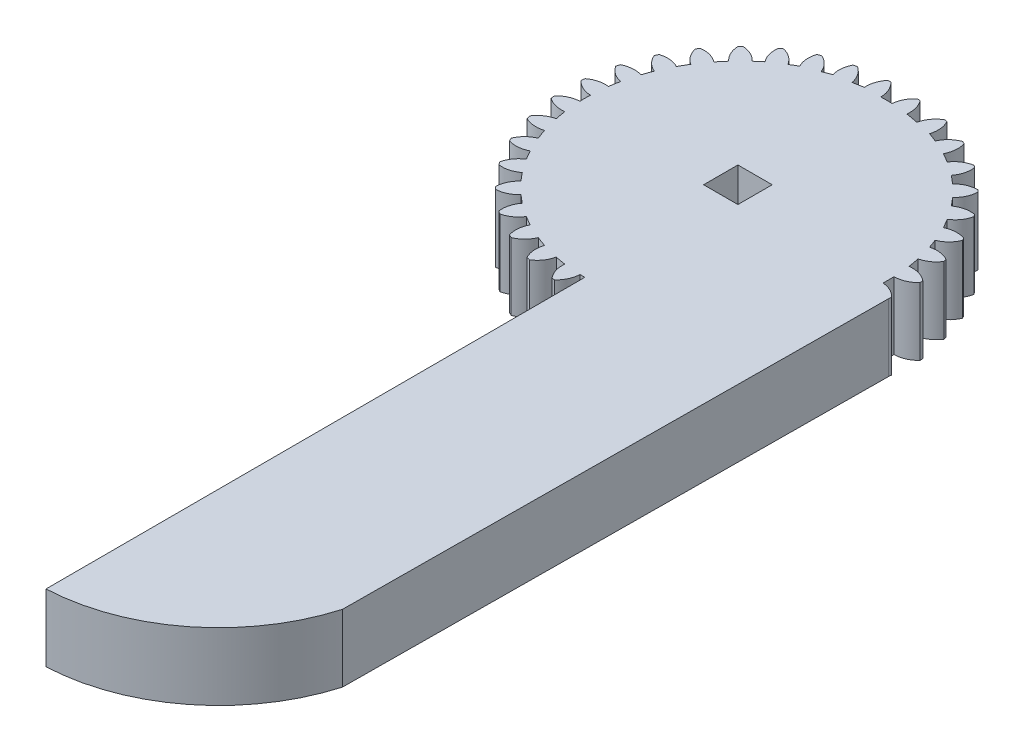
SolidWorks part; units mm, degrees
ref_plane "Front Plane" through (0, 0, 0) normal (0, 0, 1) x (1, 0, 0)
ref_plane "Top Plane" through (0, 0, 0) normal (0, 1, 0) x (1, 0, 0)
ref_plane "Right Plane" through (0, 0, 0) normal (1, 0, 0) x (0, 0, -1)
sketch "Sketch1" plane through (0, 0, 0) normal (0, 1, 0) x (1, 0, 0)
  line L1 (3.1226, 5.3296) -> (6.3526, 5.3296)
  line L2 (3.1226, 5.3296) -> (3.1226, 2.0996)
  line L3 (3.1226, 2.0996) -> (6.3526, 2.0996)
  line L4 (6.3526, 5.3296) -> (6.3526, 2.0996)
  arc A0 (-8.4629, 9.0479) -> (-8.8027, 8.1141) centre (4.7376, 3.7146) ccw
  arc A1 (-8.8027, 8.1141) -> (-10.5974, 7.9673) centre (-9.5244, 5.8929) ccw
  arc A2 (-10.5974, 7.9673) -> (-10.6872, 7.6321) centre (4.7283, 3.6812) ccw
  arc A3 (-10.6872, 7.6321) -> (-9.2064, 6.6077) centre (-8.7208, 8.8921) ccw
  arc A4 (-9.2064, 6.6077) -> (-9.3789, 5.629) centre (4.7196, 3.6476) ccw
  arc A5 (-9.3789, 5.629) -> (-11.1208, 5.1729) centre (-9.704, 3.3163) ccw
  arc A6 (-11.1208, 5.1729) -> (-11.1511, 4.8271) centre (4.7163, 3.6131) ccw
  arc A7 (-11.1511, 4.8271) -> (-9.5149, 4.0754) centre (-9.4334, 6.4094) ccw
  arc A8 (-9.5149, 4.0754) -> (-9.5149, 3.0817) centre (4.7136, 3.5785) ccw
  arc A9 (-9.5149, 3.0817) -> (-11.1511, 2.33) centre (-9.4334, 0.7476) ccw
  arc A10 (-11.1511, 2.33) -> (-11.1208, 1.9842) centre (4.7163, 3.544) ccw
  arc A11 (-11.1208, 1.9842) -> (-9.3789, 1.528) centre (-9.704, 3.8408) ccw
  arc A12 (-9.3789, 1.528) -> (-9.2064, 0.5494) centre (4.7196, 3.5095) ccw
  arc A13 (-9.2064, 0.5494) -> (-10.6872, -0.475) centre (-8.7208, -1.735) ccw
  arc A14 (-10.6872, -0.475) -> (-10.5974, -0.8103) centre (4.7283, 3.4759) ccw
  arc A15 (-10.5974, -0.8103) -> (-8.8027, -0.957) centre (-9.5244, 1.2642) ccw
  arc A16 (-8.8027, -0.957) -> (-8.4629, -1.8908) centre (4.7376, 3.4425) ccw
  arc A17 (-8.4629, -1.8908) -> (-9.7433, -3.1568) centre (-7.588, -4.0562) ccw
  arc A18 (-9.7433, -3.1568) -> (-9.5966, -3.4714) centre (4.7519, 3.4109) ccw
  arc A19 (-9.5966, -3.4714) -> (-7.8038, -3.3043) centre (-8.9002, -1.2422) ccw
  arc A20 (-7.8038, -3.3043) -> (-7.3069, -4.1649) centre (4.7669, 3.3797) ccw
  arc A21 (-7.3069, -4.1649) -> (-8.3481, -5.634) centre (-6.0693, -6.1455) ccw
  arc A22 (-8.3481, -5.634) -> (-8.149, -5.9183) centre (4.7865, 3.3511) ccw
  arc A23 (-8.149, -5.9183) -> (-6.4124, -5.4424) centre (-7.8502, -3.602) ccw
  arc A24 (-6.4124, -5.4424) -> (-5.7736, -6.2036) centre (4.8066, 3.3229) ccw
  arc A25 (-5.7736, -6.2036) -> (-6.5438, -7.8312) centre (-4.2109, -7.9392) ccw
  arc A26 (-6.5438, -7.8312) -> (-6.2984, -8.0766) centre (4.8309, 3.2981) ccw
  arc A27 (-6.2984, -8.0766) -> (-4.6708, -7.3064) centre (-6.4064, -5.7437) ccw
  arc A28 (-4.6708, -7.3064) -> (-3.9096, -7.9452) centre (4.8557, 3.2738) ccw
  arc A29 (-3.9096, -7.9452) -> (-4.3855, -9.6818) centre (-2.0692, -9.383) ccw
  arc A30 (-4.3855, -9.6818) -> (-4.1012, -9.8808) centre (4.8839, 3.2537) ccw
  arc A31 (-4.1012, -9.8808) -> (-2.6321, -8.8397) centre (-4.6127, -7.6021) ccw
  arc A32 (-2.6321, -8.8397) -> (-1.7715, -9.3365) centre (4.9124, 3.2341) ccw
  arc A33 (-1.7715, -9.3365) -> (-1.9386, -11.1294) centre (0.2906, -10.433) ccw
  arc A34 (-1.9386, -11.1294) -> (-1.624, -11.2761) centre (4.9437, 3.2191) ccw
  arc A35 (-1.624, -11.2761) -> (-0.358, -9.9956) centre (-2.5235, -9.1208) ccw
  arc A36 (-0.358, -9.9956) -> (0.5758, -10.3355) centre (4.9753, 3.2048) ccw
  arc A37 (0.5758, -10.3355) -> (0.7225, -12.1302) centre (2.7969, -11.0572) ccw
  arc A38 (0.7225, -12.1302) -> (1.0578, -12.22) centre (5.0087, 3.1955) ccw
  arc A39 (1.0578, -12.22) -> (2.0822, -10.7392) centre (-0.2023, -10.2536) ccw
  arc A40 (2.0822, -10.7392) -> (3.0608, -10.9117) centre (5.0422, 3.1868) ccw
  arc A41 (3.0608, -10.9117) -> (3.5921, -12.6536) centre (5.3836, -11.1553) ccw
  arc A42 (3.5921, -12.6536) -> (3.8688, -12.6778) centre (5.1173, 3.1868) ccw
  arc A43 (3.8688, -12.6778) -> (4.6204, -11.044) centre (2.2864, -10.9601) ccw
  arc A44 (4.6204, -11.044) -> (5.5392, -11.0416) centre (5.0423, 3.1868) ccw
  arc A45 (5.5392, -11.0416) -> (6.3659, -12.6778) centre (7.8698, -10.891) ccw
  arc A46 (6.3659, -12.6778) -> (6.6426, -12.6536) centre (5.1173, 3.1868) ccw
  arc A47 (6.6426, -12.6536) -> (7.0988, -10.9117) centre (4.786, -11.2368) ccw
  arc A48 (7.0988, -10.9117) -> (8.0035, -10.7522) centre (5.0802, 3.1816) ccw
  arc A49 (8.0035, -10.7522) -> (9.0949, -12.2151) centre (10.2723, -10.1981) ccw
  arc A50 (9.0949, -12.2151) -> (9.3632, -12.1432) centre (5.1104, 3.1918) ccw
  arc A51 (9.3632, -12.1432) -> (9.5099, -10.3485) centre (7.2888, -11.0702) ccw
  arc A52 (9.5099, -10.3485) -> (10.3733, -10.0343) centre (5.0748, 3.1801) ccw
  arc A53 (10.3733, -10.0343) -> (11.7064, -11.297) centre (12.5166, -9.1066) ccw
  arc A54 (11.7064, -11.297) -> (11.9581, -11.1796) centre (5.107, 3.1839) ccw
  arc A55 (11.9581, -11.1796) -> (11.7983, -9.4007) centre (9.7289, -10.4832) ccw
  arc A56 (11.7983, -9.4007) -> (12.5474, -8.9681) centre (5.0568, 3.1392) ccw
  arc A57 (12.5474, -8.9681) -> (14.0856, -9.9905) centre (14.5039, -7.6928) ccw
  arc A58 (14.0856, -9.9905) -> (14.3131, -9.8312) centre (5.072, 3.1244) ccw
  arc A59 (14.3131, -9.8312) -> (13.8524, -8.1143) centre (11.9968, -9.5324) ccw
  arc A60 (13.8524, -8.1143) -> (14.5276, -7.5474) centre (5.0396, 3.0673) ccw
  arc A61 (14.5276, -7.5474) -> (16.2323, -8.3032) centre (16.2479, -5.9678) ccw
  arc A62 (16.2323, -8.3032) -> (16.4287, -8.1069) centre (5.0782, 3.0472) ccw
  arc A63 (16.4287, -8.1069) -> (15.6928, -6.5108) centre (14.0957, -8.2149) ccw
  arc A64 (15.6928, -6.5108) -> (16.2617, -5.8331) centre (5.0782, 2.9773) ccw
  arc A65 (16.2617, -5.8331) -> (18.083, -6.2906) centre (17.6933, -3.9879) ccw
  arc A66 (18.083, -6.2906) -> (18.2423, -6.0631) centre (5.1274, 2.9505) ccw
  arc A67 (18.2423, -6.0631) -> (17.2416, -4.6199) centre (15.9635, -6.5746) ccw
  arc A68 (17.2416, -4.6199) -> (17.6956, -3.8334) centre (5.1448, 2.8877) ccw
  arc A69 (17.6956, -3.8334) -> (19.5697, -3.9701) centre (18.7882, -1.7693) ccw
  arc A70 (19.5697, -3.9701) -> (19.6871, -3.7184) centre (5.2062, 2.8809) ccw
  arc A71 (19.6871, -3.7184) -> (18.4655, -2.4771) centre (17.5318, -4.6178) ccw
  arc A72 (18.4655, -2.4771) -> (19.0015, -1.58) centre (6.5204, 5.2696) ccw
  arc A73 (19.0015, -1.58) -> (20.7489, -1.3501) centre (19.5931, 0.6793) ccw
  arc A74 (20.7489, -1.3501) -> (20.8208, -1.0819) centre (5.4139, 2.9026) ccw
  arc A75 (20.8208, -1.0819) -> (19.2773, -0.045) centre (18.8543, -2.3419) ccw
  arc A76 (19.2773, -0.045) -> (19.457, 0.9703) centre (5.3571, 2.9424) ccw
  arc A77 (19.457, 0.9703) -> (21.1306, 1.505) centre (19.6353, 3.299) ccw
  arc A78 (21.1306, 1.505) -> (21.1548, 1.7816) centre (5.2902, 3.0302) ccw
  arc A79 (21.1548, 1.7816) -> (19.588, 2.5299) centre (19.4371, 0.1993) ccw
  arc A80 (19.588, 2.5299) -> (19.5887, 3.5643) centre (5.3606, 3.0559) ccw
  arc A81 (19.5887, 3.5643) -> (21.2992, 4.3175) centre (19.5814, 5.8998) ccw
  arc A82 (21.2992, 4.3175) -> (21.275, 4.5942) centre (5.4345, 3.0689) ccw
  arc A83 (21.275, 4.5942) -> (19.4527, 5.118) centre (19.7742, 2.8047) ccw
  arc A84 (19.4527, 5.118) -> (19.2696, 6.1496) centre (5.3525, 3.1481) ccw
  arc A85 (19.2696, 6.1496) -> (20.6965, 7.1618) centre (18.7301, 8.4219) ccw
  arc A86 (20.6965, 7.1618) -> (20.6246, 7.4301) centre (5.2896, 3.1774) ccw
  arc A87 (20.6246, 7.4301) -> (18.8522, 7.6522) centre (19.4701, 5.4) ccw
  arc A88 (18.8522, 7.6522) -> (18.5545, 8.4711) centre (5.329, 3.2004) ccw
  arc A89 (18.5545, 8.4711) -> (19.8496, 9.743) centre (17.6943, 10.6424) ccw
  arc A90 (19.8496, 9.743) -> (19.7322, 9.9947) centre (5.3687, 3.1436) ccw
  arc A91 (19.7322, 9.9947) -> (17.9104, 9.8914) centre (18.943, 7.7966) ccw
  arc A92 (17.9104, 9.8914) -> (17.4135, 10.752) centre (5.3398, 3.2075) ccw
  arc A93 (17.4135, 10.752) -> (18.4547, 12.2211) centre (16.1759, 12.7326) ccw
  arc A94 (18.4547, 12.2211) -> (18.2954, 12.4487) centre (5.3398, 3.2075) ccw
  arc A95 (18.2954, 12.4487) -> (16.519, 12.0295) centre (17.9009, 10.1467) ccw
  arc A96 (16.519, 12.0295) -> (15.8803, 12.7908) centre (5.3, 3.2643) ccw
  arc A97 (15.8803, 12.7908) -> (16.6505, 14.4184) centre (14.3175, 14.5264) ccw
  arc A98 (16.6505, 14.4184) -> (16.4541, 14.6148) centre (5.3, 3.2643) ccw
  arc A99 (16.4541, 14.6148) -> (14.7775, 13.8936) centre (16.4653, 12.2793) ccw
  arc A100 (14.7775, 13.8936) -> (14.0162, 14.5323) centre (5.251, 3.3133) ccw
  arc A101 (14.0162, 14.5323) -> (14.4921, 16.2689) centre (12.1759, 15.9702) ccw
  arc A102 (14.4921, 16.2689) -> (14.2646, 16.4282) centre (5.251, 3.3133) ccw
  arc A103 (14.2646, 16.4282) -> (12.7387, 15.4268) centre (14.6812, 14.1302) ccw
  arc A104 (12.7387, 15.4268) -> (11.8781, 15.9237) centre (5.1942, 3.3531) ccw
  arc A105 (11.8781, 15.9237) -> (12.0452, 17.7166) centre (9.816, 17.0201) ccw
  arc A106 (12.0452, 17.7166) -> (11.7935, 17.834) centre (5.1942, 3.3531) ccw
  arc A107 (11.7935, 17.834) -> (10.4647, 16.5828) centre (12.6028, 15.6432) ccw
  arc A108 (10.4647, 16.5828) -> (9.5963, 16.9013) centre (5.1314, 3.3824) ccw
  arc A109 (9.5963, 16.9013) -> (9.447, 18.688) centre (7.3725, 17.6151) ccw
  arc A110 (9.447, 18.688) -> (9.1787, 18.7599) centre (5.1942, 3.3531) ccw
  arc A111 (9.1787, 18.7599) -> (8.0731, 17.2362) centre (10.3559, 16.7428) ccw
  arc A112 (8.0731, 17.2362) -> (6.9219, 17.4412) centre (5.0039, 3.3339) ccw
  arc A113 (6.9219, 17.4412) -> (6.4622, 19.1564) centre (4.6056, 17.7395) ccw
  arc A114 (6.4622, 19.1564) -> (6.1855, 19.1806) centre (4.9369, 3.3159) ccw
  arc A115 (6.1855, 19.1806) -> (5.3712, 17.6066) centre (7.6975, 17.4007) ccw
  arc A116 (5.3712, 17.6066) -> (4.3071, 17.6071) centre (4.8319, 3.3797) ccw
  arc A117 (4.3071, 17.6071) -> (3.5541, 19.3072) centre (1.9717, 17.5894) ccw
  arc A118 (3.5541, 19.3072) -> (3.2774, 19.283) centre (4.8026, 3.4425) ccw
  arc A119 (3.2774, 19.283) -> (2.7476, 17.6093) centre (5.0758, 17.793) ccw
  arc A120 (2.7476, 17.6093) -> (1.7668, 17.437) centre (4.7196, 3.5095) ccw
  arc A121 (1.7668, 17.437) -> (0.7291, 18.9854) centre (-0.5309, 17.019) ccw
  arc A122 (0.7291, 18.9854) -> (0.3962, 18.9022) centre (4.4202, 3.5056) ccw
  arc A123 (0.3962, 18.9022) -> (0.2306, 17.1685) centre (2.4706, 17.8292) ccw
  arc A124 (0.2306, 17.1685) -> (-0.5756, 16.8633) centre (4.8649, 3.7067) ccw
  arc A125 (-0.5756, 16.8633) -> (-1.8618, 18.1954) centre (-2.7612, 16.0401) ccw
  arc A126 (-1.8618, 18.1954) -> (-2.1768, 18.0534) centre (4.5211, 3.6178) ccw
  arc A127 (-2.1768, 18.0534) -> (-2.0289, 16.2975) centre (0.0524, 17.357) ccw
  arc A128 (-2.0289, 16.2975) -> (-2.7236, 15.8848) centre (4.892, 3.8557) ccw
  arc A129 (-2.7236, 15.8848) -> (-4.207, 16.9491) centre (-4.7185, 14.6703) ccw
  arc A130 (-4.207, 16.9491) -> (-4.4929, 16.751) centre (4.7146, 3.7714) ccw
  arc A131 (-4.4929, 16.751) -> (-4.022, 15.0209) centre (-2.1766, 16.4522) ccw
  arc A132 (-4.022, 15.0209) -> (-4.6708, 14.4634) centre (4.9277, 3.9485) ccw
  arc A133 (-4.6708, 14.4634) -> (-6.2984, 15.2337) centre (-6.4064, 12.9007) ccw
  arc A134 (-6.2984, 15.2337) -> (-6.5438, 14.9883) centre (4.8309, 3.8589) ccw
  arc A135 (-6.5438, 14.9883) -> (-5.7736, 13.3607) centre (-4.2109, 15.0963) ccw
  arc A136 (-5.7736, 13.3607) -> (-6.4124, 12.5994) centre (4.8066, 3.8342) ccw
  arc A137 (-6.4124, 12.5994) -> (-8.149, 13.0753) centre (-7.8502, 10.759) ccw
  arc A138 (-8.149, 13.0753) -> (-8.3481, 12.791) centre (4.7865, 3.806) ccw
  arc A139 (-8.3481, 12.791) -> (-7.3069, 11.3219) centre (-6.0693, 13.3025) ccw
  arc A140 (-7.3069, 11.3219) -> (-7.8038, 10.4613) centre (4.7669, 3.7774) ccw
  arc A141 (-7.8038, 10.4613) -> (-9.5966, 10.6284) centre (-8.9002, 8.3992) ccw
  arc A142 (-9.5966, 10.6284) -> (-9.7433, 10.3139) centre (4.7519, 3.7461) ccw
  arc A143 (-9.7433, 10.3139) -> (-8.4629, 9.0479) centre (-7.588, 11.2133) ccw
  point P288 (0, 0)
  dimension "D6" = 1.5596
  dimension "D33" = 1.5596
  dimension "D39" = 1.5596
  dimension "D1" = 3.23
  dimension "D2" = 3.23
  dimension "D3" = 1.615
  dimension "D4" = 1.615
  dimension "D5" = 1.5596
  dimension "D7" = 1.5596
  dimension "D8" = 1.5596
  dimension "D9" = 1.5596
  dimension "D10" = 1.5596
  dimension "D11" = 1.5596
  dimension "D12" = 1.5596
  dimension "D13" = 1.5596
  dimension "D14" = 1.5596
  dimension "D15" = 1.5596
  dimension "D16" = 1.5596
  dimension "D17" = 1.5596
  dimension "D18" = 1.5596
  dimension "D19" = 1.5596
  dimension "D20" = 1.5596
  dimension "D21" = 1.5596
  dimension "D22" = 1.5596
  dimension "D23" = 1.5596
  dimension "D24" = 1.5596
  dimension "D25" = 1.5596
  dimension "D26" = 1.5596
  dimension "D27" = 1.5596
  dimension "D28" = 1.5596
  dimension "D29" = 1.5596
  dimension "D30" = 1.5596
  dimension "D31" = 1.5596
  dimension "D32" = 1.5596
  dimension "D34" = 1.5596
  dimension "D35" = 1.5596
  dimension "D36" = 1.5596
  dimension "D37" = 1.5596
  dimension "D38" = 1.5596
  dimension "D40" = 1.5596
extrude "Boss-Extrude1" add sketch "Sketch1" along normal blind 6.35
sketch "Sketch3" plane through (0, 6.35, 0) normal (0, 1, 0) x (1, 0, 0)
  line L0 (5.1234, -61.85) -> (5.0798, -11.0502)
  line L1 (20.7489, -49.5398) -> (21.1306, 1.505)
  arc A0 (5.1234, -61.85) -> (20.7489, -49.5398) centre (4.3767, -44.8304) ccw
  arc A144 (-9.7433, 10.3139) -> (-8.4629, 9.0479) centre (-7.588, 11.2133) ccw
  arc A145 (-8.4629, 9.0479) -> (-8.8027, 8.1141) centre (4.7376, 3.7146) ccw
  arc A146 (-8.8027, 8.1141) -> (-10.5974, 7.9673) centre (-9.5244, 5.8929) ccw
  arc A147 (-10.5974, 7.9673) -> (-10.6872, 7.6321) centre (4.7283, 3.6812) ccw
  arc A148 (-10.6872, 7.6321) -> (-9.2064, 6.6077) centre (-8.7208, 8.8921) ccw
  arc A149 (-9.2064, 6.6077) -> (-9.3789, 5.629) centre (4.7196, 3.6476) ccw
  arc A150 (-9.3789, 5.629) -> (-11.1208, 5.1729) centre (-9.704, 3.3163) ccw
  arc A151 (-11.1208, 5.1729) -> (-11.1511, 4.8271) centre (4.7163, 3.6131) ccw
  arc A152 (-11.1511, 4.8271) -> (-9.5149, 4.0754) centre (-9.4334, 6.4094) ccw
  arc A153 (-9.5149, 4.0754) -> (-9.5149, 3.0817) centre (4.7136, 3.5785) ccw
  arc A154 (-9.5149, 3.0817) -> (-11.1511, 2.33) centre (-9.4334, 0.7476) ccw
  arc A155 (-11.1511, 2.33) -> (-11.1208, 1.9842) centre (4.7163, 3.544) ccw
  arc A156 (-11.1208, 1.9842) -> (-9.3789, 1.528) centre (-9.704, 3.8408) ccw
  arc A157 (-9.3789, 1.528) -> (-9.2064, 0.5494) centre (4.7196, 3.5095) ccw
  arc A158 (-9.2064, 0.5494) -> (-10.6872, -0.475) centre (-8.7208, -1.735) ccw
  arc A159 (-10.6872, -0.475) -> (-10.5974, -0.8103) centre (4.7283, 3.4759) ccw
  arc A160 (-10.5974, -0.8103) -> (-8.8027, -0.957) centre (-9.5244, 1.2642) ccw
  arc A161 (-8.8027, -0.957) -> (-8.4629, -1.8908) centre (4.7376, 3.4425) ccw
  arc A162 (-8.4629, -1.8908) -> (-9.7433, -3.1568) centre (-7.588, -4.0562) ccw
  arc A163 (-9.7433, -3.1568) -> (-9.5966, -3.4714) centre (4.7519, 3.4109) ccw
  arc A164 (-9.5966, -3.4714) -> (-7.8038, -3.3043) centre (-8.9002, -1.2422) ccw
  arc A165 (-7.8038, -3.3043) -> (-7.3069, -4.1649) centre (4.7669, 3.3797) ccw
  arc A166 (-7.3069, -4.1649) -> (-8.3481, -5.634) centre (-6.0693, -6.1455) ccw
  arc A167 (-8.3481, -5.634) -> (-8.149, -5.9183) centre (4.7865, 3.3511) ccw
  arc A168 (-8.149, -5.9183) -> (-6.4124, -5.4424) centre (-7.8502, -3.602) ccw
  arc A169 (-6.4124, -5.4424) -> (-5.7736, -6.2036) centre (4.8066, 3.3229) ccw
  arc A170 (-5.7736, -6.2036) -> (-6.5438, -7.8312) centre (-4.2109, -7.9392) ccw
  arc A171 (-6.5438, -7.8312) -> (-6.2984, -8.0766) centre (4.8309, 3.2981) ccw
  arc A172 (-6.2984, -8.0766) -> (-4.6708, -7.3064) centre (-6.4064, -5.7437) ccw
  arc A173 (-4.6708, -7.3064) -> (-3.9096, -7.9452) centre (4.8557, 3.2738) ccw
  arc A174 (-3.9096, -7.9452) -> (-4.3855, -9.6818) centre (-2.0692, -9.383) ccw
  arc A175 (-4.3855, -9.6818) -> (-4.1012, -9.8808) centre (4.8839, 3.2537) ccw
  arc A176 (-4.1012, -9.8808) -> (-2.6321, -8.8397) centre (-4.6127, -7.6021) ccw
  arc A177 (-2.6321, -8.8397) -> (-1.7715, -9.3365) centre (4.9124, 3.2341) ccw
  arc A178 (-1.7715, -9.3365) -> (-1.9386, -11.1294) centre (0.2906, -10.433) ccw
  arc A179 (-1.9386, -11.1294) -> (-1.624, -11.2761) centre (4.9437, 3.2191) ccw
  arc A180 (-1.624, -11.2761) -> (-0.358, -9.9956) centre (-2.5235, -9.1208) ccw
  arc A181 (-0.358, -9.9956) -> (0.5758, -10.3355) centre (4.9753, 3.2048) ccw
  arc A182 (0.5758, -10.3355) -> (0.7225, -12.1302) centre (2.7969, -11.0572) ccw
  arc A183 (0.7225, -12.1302) -> (1.0578, -12.22) centre (5.0087, 3.1955) ccw
  arc A184 (1.0578, -12.22) -> (2.0822, -10.7392) centre (-0.2023, -10.2536) ccw
  arc A185 (2.0822, -10.7392) -> (3.0608, -10.9117) centre (5.0422, 3.1868) ccw
  arc A186 (3.0608, -10.9117) -> (3.5921, -12.6536) centre (5.3836, -11.1553) ccw
  arc A187 (3.5921, -12.6536) -> (3.8688, -12.6778) centre (5.1173, 3.1868) ccw
  arc A188 (3.8688, -12.6778) -> (4.6204, -11.044) centre (2.2864, -10.9601) ccw
  arc A189 (4.6204, -11.044) -> (5.5392, -11.0416) centre (5.0423, 3.1868) ccw
  arc A190 (5.5392, -11.0416) -> (6.3659, -12.6778) centre (7.8698, -10.891) ccw
  arc A191 (6.3659, -12.6778) -> (6.6426, -12.6536) centre (5.1173, 3.1868) ccw
  arc A192 (6.6426, -12.6536) -> (7.0988, -10.9117) centre (4.786, -11.2368) ccw
  arc A193 (7.0988, -10.9117) -> (8.0035, -10.7522) centre (5.0802, 3.1816) ccw
  arc A194 (8.0035, -10.7522) -> (9.0949, -12.2151) centre (10.2723, -10.1981) ccw
  arc A195 (9.0949, -12.2151) -> (9.3632, -12.1432) centre (5.1104, 3.1918) ccw
  arc A196 (9.3632, -12.1432) -> (9.5099, -10.3485) centre (7.2888, -11.0702) ccw
  arc A197 (9.5099, -10.3485) -> (10.3733, -10.0343) centre (5.0748, 3.1801) ccw
  arc A198 (10.3733, -10.0343) -> (11.7064, -11.297) centre (12.5166, -9.1066) ccw
  arc A199 (11.7064, -11.297) -> (11.9581, -11.1796) centre (5.107, 3.1839) ccw
  arc A200 (11.9581, -11.1796) -> (11.7983, -9.4007) centre (9.7289, -10.4832) ccw
  arc A201 (11.7983, -9.4007) -> (12.5474, -8.9681) centre (5.0568, 3.1392) ccw
  arc A202 (12.5474, -8.9681) -> (14.0856, -9.9905) centre (14.5039, -7.6928) ccw
  arc A203 (14.0856, -9.9905) -> (14.3131, -9.8312) centre (5.072, 3.1244) ccw
  arc A204 (14.3131, -9.8312) -> (13.8524, -8.1143) centre (11.9968, -9.5324) ccw
  arc A205 (13.8524, -8.1143) -> (14.5276, -7.5474) centre (5.0396, 3.0673) ccw
  arc A206 (14.5276, -7.5474) -> (16.2323, -8.3032) centre (16.2479, -5.9678) ccw
  arc A207 (16.2323, -8.3032) -> (16.4287, -8.1069) centre (5.0782, 3.0472) ccw
  arc A208 (16.4287, -8.1069) -> (15.6928, -6.5108) centre (14.0957, -8.2149) ccw
  arc A209 (15.6928, -6.5108) -> (16.2617, -5.8331) centre (5.0782, 2.9773) ccw
  arc A210 (16.2617, -5.8331) -> (18.083, -6.2906) centre (17.6933, -3.9879) ccw
  arc A211 (18.083, -6.2906) -> (18.2423, -6.0631) centre (5.1274, 2.9505) ccw
  arc A212 (18.2423, -6.0631) -> (17.2416, -4.6199) centre (15.9635, -6.5746) ccw
  arc A213 (17.2416, -4.6199) -> (17.6956, -3.8334) centre (5.1448, 2.8877) ccw
  arc A214 (17.6956, -3.8334) -> (19.5697, -3.9701) centre (18.7882, -1.7693) ccw
  arc A215 (19.5697, -3.9701) -> (19.6871, -3.7184) centre (5.2062, 2.8809) ccw
  arc A216 (19.6871, -3.7184) -> (18.4655, -2.4771) centre (17.5318, -4.6178) ccw
  arc A217 (18.4655, -2.4771) -> (19.0015, -1.58) centre (6.5204, 5.2696) ccw
  arc A218 (19.0015, -1.58) -> (20.7489, -1.3501) centre (19.5931, 0.6793) ccw
  arc A219 (20.7489, -1.3501) -> (20.8208, -1.0819) centre (5.4139, 2.9026) ccw
  arc A220 (20.8208, -1.0819) -> (19.2773, -0.045) centre (18.8543, -2.3419) ccw
  arc A221 (19.2773, -0.045) -> (19.457, 0.9703) centre (5.3571, 2.9424) ccw
  arc A222 (19.457, 0.9703) -> (21.1306, 1.505) centre (19.6353, 3.299) ccw
  arc A223 (21.1306, 1.505) -> (21.1548, 1.7816) centre (5.2902, 3.0302) ccw
  arc A224 (21.1548, 1.7816) -> (19.588, 2.5299) centre (19.4371, 0.1993) ccw
  arc A225 (19.588, 2.5299) -> (19.5887, 3.5643) centre (5.3606, 3.0559) ccw
  arc A226 (19.5887, 3.5643) -> (21.2992, 4.3175) centre (19.5814, 5.8998) ccw
  arc A227 (21.2992, 4.3175) -> (21.275, 4.5942) centre (5.4345, 3.0689) ccw
  arc A228 (21.275, 4.5942) -> (19.4527, 5.118) centre (19.7742, 2.8047) ccw
  arc A229 (19.4527, 5.118) -> (19.2696, 6.1496) centre (5.3525, 3.1481) ccw
  arc A230 (19.2696, 6.1496) -> (20.6965, 7.1618) centre (18.7301, 8.4219) ccw
  arc A231 (20.6965, 7.1618) -> (20.6246, 7.4301) centre (5.2896, 3.1774) ccw
  arc A232 (20.6246, 7.4301) -> (18.8522, 7.6522) centre (19.4701, 5.4) ccw
  arc A233 (18.8522, 7.6522) -> (18.5545, 8.4711) centre (5.329, 3.2004) ccw
  arc A234 (18.5545, 8.4711) -> (19.8496, 9.743) centre (17.6943, 10.6424) ccw
  arc A235 (19.8496, 9.743) -> (19.7322, 9.9947) centre (5.3687, 3.1436) ccw
  arc A236 (19.7322, 9.9947) -> (17.9104, 9.8914) centre (18.943, 7.7966) ccw
  arc A237 (17.9104, 9.8914) -> (17.4135, 10.752) centre (5.3398, 3.2075) ccw
  arc A238 (17.4135, 10.752) -> (18.4547, 12.2211) centre (16.1759, 12.7326) ccw
  arc A239 (18.4547, 12.2211) -> (18.2954, 12.4487) centre (5.3398, 3.2075) ccw
  arc A240 (18.2954, 12.4487) -> (16.519, 12.0295) centre (17.9009, 10.1467) ccw
  arc A241 (16.519, 12.0295) -> (15.8803, 12.7908) centre (5.3, 3.2643) ccw
  arc A242 (15.8803, 12.7908) -> (16.6505, 14.4184) centre (14.3175, 14.5264) ccw
  arc A243 (16.6505, 14.4184) -> (16.4541, 14.6148) centre (5.3, 3.2643) ccw
  arc A244 (16.4541, 14.6148) -> (14.7775, 13.8936) centre (16.4653, 12.2793) ccw
  arc A245 (14.7775, 13.8936) -> (14.0162, 14.5323) centre (5.251, 3.3133) ccw
  arc A246 (14.0162, 14.5323) -> (14.4921, 16.2689) centre (12.1759, 15.9702) ccw
  arc A247 (14.4921, 16.2689) -> (14.2646, 16.4282) centre (5.251, 3.3133) ccw
  arc A248 (14.2646, 16.4282) -> (12.7387, 15.4268) centre (14.6812, 14.1302) ccw
  arc A249 (12.7387, 15.4268) -> (11.8781, 15.9237) centre (5.1942, 3.3531) ccw
  arc A250 (11.8781, 15.9237) -> (12.0452, 17.7166) centre (9.816, 17.0201) ccw
  arc A251 (12.0452, 17.7166) -> (11.7935, 17.834) centre (5.1942, 3.3531) ccw
  arc A252 (11.7935, 17.834) -> (10.4647, 16.5828) centre (12.6028, 15.6432) ccw
  arc A253 (10.4647, 16.5828) -> (9.5963, 16.9013) centre (5.1314, 3.3824) ccw
  arc A254 (9.5963, 16.9013) -> (9.447, 18.688) centre (7.3725, 17.6151) ccw
  arc A255 (9.447, 18.688) -> (9.1787, 18.7599) centre (5.1942, 3.3531) ccw
  arc A256 (9.1787, 18.7599) -> (8.0731, 17.2362) centre (10.3559, 16.7428) ccw
  arc A257 (8.0731, 17.2362) -> (6.9219, 17.4412) centre (5.0039, 3.3339) ccw
  arc A258 (6.9219, 17.4412) -> (6.4622, 19.1564) centre (4.6056, 17.7395) ccw
  arc A259 (6.4622, 19.1564) -> (6.1855, 19.1806) centre (4.9369, 3.3159) ccw
  arc A260 (6.1855, 19.1806) -> (5.3712, 17.6066) centre (7.6975, 17.4007) ccw
  arc A261 (5.3712, 17.6066) -> (4.3071, 17.6071) centre (4.8319, 3.3797) ccw
  arc A262 (4.3071, 17.6071) -> (3.5541, 19.3072) centre (1.9717, 17.5894) ccw
  arc A263 (3.5541, 19.3072) -> (3.2774, 19.283) centre (4.8026, 3.4425) ccw
  arc A264 (3.2774, 19.283) -> (2.7476, 17.6093) centre (5.0758, 17.793) ccw
  arc A265 (2.7476, 17.6093) -> (1.7668, 17.437) centre (4.7196, 3.5095) ccw
  arc A266 (1.7668, 17.437) -> (0.7291, 18.9854) centre (-0.5309, 17.019) ccw
  arc A267 (0.7291, 18.9854) -> (0.3962, 18.9022) centre (4.4202, 3.5056) ccw
  arc A268 (0.3962, 18.9022) -> (0.2306, 17.1685) centre (2.4706, 17.8292) ccw
  arc A269 (0.2306, 17.1685) -> (-0.5756, 16.8633) centre (4.8649, 3.7067) ccw
  arc A270 (-0.5756, 16.8633) -> (-1.8618, 18.1954) centre (-2.7612, 16.0401) ccw
  arc A271 (-1.8618, 18.1954) -> (-2.1768, 18.0534) centre (4.5211, 3.6178) ccw
  arc A272 (-2.1768, 18.0534) -> (-2.0289, 16.2975) centre (0.0524, 17.357) ccw
  arc A273 (-2.0289, 16.2975) -> (-2.7236, 15.8848) centre (4.892, 3.8557) ccw
  arc A274 (-2.7236, 15.8848) -> (-4.207, 16.9491) centre (-4.7185, 14.6703) ccw
  arc A275 (-4.207, 16.9491) -> (-4.4929, 16.751) centre (4.7146, 3.7714) ccw
  arc A276 (-4.4929, 16.751) -> (-4.022, 15.0209) centre (-2.1766, 16.4522) ccw
  arc A277 (-4.022, 15.0209) -> (-4.6708, 14.4634) centre (4.9277, 3.9485) ccw
  arc A278 (-4.6708, 14.4634) -> (-6.2984, 15.2337) centre (-6.4064, 12.9007) ccw
  arc A279 (-6.2984, 15.2337) -> (-6.5438, 14.9883) centre (4.8309, 3.8589) ccw
  arc A280 (-6.5438, 14.9883) -> (-5.7736, 13.3607) centre (-4.2109, 15.0963) ccw
  arc A281 (-5.7736, 13.3607) -> (-6.4124, 12.5994) centre (4.8066, 3.8342) ccw
  arc A282 (-6.4124, 12.5994) -> (-8.149, 13.0753) centre (-7.8502, 10.759) ccw
  arc A283 (-8.149, 13.0753) -> (-8.3481, 12.791) centre (4.7865, 3.806) ccw
  arc A284 (-8.3481, 12.791) -> (-7.3069, 11.3219) centre (-6.0693, 13.3025) ccw
  arc A285 (-7.3069, 11.3219) -> (-7.8038, 10.4613) centre (4.7669, 3.7774) ccw
  arc A286 (-7.8038, 10.4613) -> (-9.5966, 10.6284) centre (-8.9002, 8.3992) ccw
  arc A287 (-9.5966, 10.6284) -> (-9.7433, 10.3139) centre (4.7519, 3.7461) ccw
  arc A288 (-9.7433, 10.3139) -> (-8.4629, 9.0479) centre (-7.588, 11.2133) ccw
  arc A289 (-8.4629, 9.0479) -> (-8.8027, 8.1141) centre (4.7376, 3.7146) ccw
  arc A290 (-8.8027, 8.1141) -> (-10.5974, 7.9673) centre (-9.5244, 5.8929) ccw
  arc A291 (-10.5974, 7.9673) -> (-10.6872, 7.6321) centre (4.7283, 3.6812) ccw
  arc A292 (-10.6872, 7.6321) -> (-9.2064, 6.6077) centre (-8.7208, 8.8921) ccw
  arc A293 (-9.2064, 6.6077) -> (-9.3789, 5.629) centre (4.7196, 3.6476) ccw
  arc A294 (-9.3789, 5.629) -> (-11.1208, 5.1729) centre (-9.704, 3.3163) ccw
  arc A295 (-11.1208, 5.1729) -> (-11.1511, 4.8271) centre (4.7163, 3.6131) ccw
  arc A296 (-11.1511, 4.8271) -> (-9.5149, 4.0754) centre (-9.4334, 6.4094) ccw
  arc A297 (-9.5149, 4.0754) -> (-9.5149, 3.0817) centre (4.7136, 3.5785) ccw
  arc A298 (-9.5149, 3.0817) -> (-11.1511, 2.33) centre (-9.4334, 0.7476) ccw
  arc A299 (-11.1511, 2.33) -> (-11.1208, 1.9842) centre (4.7163, 3.544) ccw
  arc A300 (-11.1208, 1.9842) -> (-9.3789, 1.528) centre (-9.704, 3.8408) ccw
  arc A301 (-9.3789, 1.528) -> (-9.2064, 0.5494) centre (4.7196, 3.5095) ccw
  arc A302 (-9.2064, 0.5494) -> (-10.6872, -0.475) centre (-8.7208, -1.735) ccw
  arc A303 (-10.6872, -0.475) -> (-10.5974, -0.8103) centre (4.7283, 3.4759) ccw
  arc A304 (-10.5974, -0.8103) -> (-8.8027, -0.957) centre (-9.5244, 1.2642) ccw
  arc A305 (-8.8027, -0.957) -> (-8.4629, -1.8908) centre (4.7376, 3.4425) ccw
  arc A306 (-8.4629, -1.8908) -> (-9.7433, -3.1568) centre (-7.588, -4.0562) ccw
  arc A307 (-9.7433, -3.1568) -> (-9.5966, -3.4714) centre (4.7519, 3.4109) ccw
  arc A308 (-9.5966, -3.4714) -> (-7.8038, -3.3043) centre (-8.9002, -1.2422) ccw
  arc A309 (-7.8038, -3.3043) -> (-7.3069, -4.1649) centre (4.7669, 3.3797) ccw
  arc A310 (-7.3069, -4.1649) -> (-8.3481, -5.634) centre (-6.0693, -6.1455) ccw
  arc A311 (-8.3481, -5.634) -> (-8.149, -5.9183) centre (4.7865, 3.3511) ccw
  arc A312 (-8.149, -5.9183) -> (-6.4124, -5.4424) centre (-7.8502, -3.602) ccw
  arc A313 (-6.4124, -5.4424) -> (-5.7736, -6.2036) centre (4.8066, 3.3229) ccw
  arc A314 (-5.7736, -6.2036) -> (-6.5438, -7.8312) centre (-4.2109, -7.9392) ccw
  arc A315 (-6.5438, -7.8312) -> (-6.2984, -8.0766) centre (4.8309, 3.2981) ccw
  arc A316 (-6.2984, -8.0766) -> (-4.6708, -7.3064) centre (-6.4064, -5.7437) ccw
  arc A317 (-4.6708, -7.3064) -> (-3.9096, -7.9452) centre (4.8557, 3.2738) ccw
  arc A318 (-3.9096, -7.9452) -> (-4.3855, -9.6818) centre (-2.0692, -9.383) ccw
  arc A319 (-4.3855, -9.6818) -> (-4.1012, -9.8808) centre (4.8839, 3.2537) ccw
  arc A320 (-4.1012, -9.8808) -> (-2.6321, -8.8397) centre (-4.6127, -7.6021) ccw
  arc A321 (-2.6321, -8.8397) -> (-1.7715, -9.3365) centre (4.9124, 3.2341) ccw
  arc A322 (-1.7715, -9.3365) -> (-1.9386, -11.1294) centre (0.2906, -10.433) ccw
  arc A323 (-1.9386, -11.1294) -> (-1.624, -11.2761) centre (4.9437, 3.2191) ccw
  arc A324 (-1.624, -11.2761) -> (-0.358, -9.9956) centre (-2.5235, -9.1208) ccw
  arc A325 (-0.358, -9.9956) -> (0.5758, -10.3355) centre (4.9753, 3.2048) ccw
  arc A326 (0.5758, -10.3355) -> (0.7225, -12.1302) centre (2.7969, -11.0572) ccw
  arc A327 (0.7225, -12.1302) -> (1.0578, -12.22) centre (5.0087, 3.1955) ccw
  arc A328 (1.0578, -12.22) -> (2.0822, -10.7392) centre (-0.2023, -10.2536) ccw
  arc A329 (2.0822, -10.7392) -> (3.0608, -10.9117) centre (5.0422, 3.1868) ccw
  arc A330 (3.0608, -10.9117) -> (3.5921, -12.6536) centre (5.3836, -11.1553) ccw
  arc A331 (3.5921, -12.6536) -> (3.8688, -12.6778) centre (5.1173, 3.1868) ccw
  arc A332 (3.8688, -12.6778) -> (4.6204, -11.044) centre (2.2864, -10.9601) ccw
  arc A333 (4.6204, -11.044) -> (5.5392, -11.0416) centre (5.0423, 3.1868) ccw
  arc A334 (5.5392, -11.0416) -> (6.3659, -12.6778) centre (7.8698, -10.891) ccw
  arc A335 (6.3659, -12.6778) -> (6.6426, -12.6536) centre (5.1173, 3.1868) ccw
  arc A336 (6.6426, -12.6536) -> (7.0988, -10.9117) centre (4.786, -11.2368) ccw
  arc A337 (7.0988, -10.9117) -> (8.0035, -10.7522) centre (5.0802, 3.1816) ccw
  arc A338 (8.0035, -10.7522) -> (9.0949, -12.2151) centre (10.2723, -10.1981) ccw
  arc A339 (9.0949, -12.2151) -> (9.3632, -12.1432) centre (5.1104, 3.1918) ccw
  arc A340 (9.3632, -12.1432) -> (9.5099, -10.3485) centre (7.2888, -11.0702) ccw
  arc A341 (9.5099, -10.3485) -> (10.3733, -10.0343) centre (5.0748, 3.1801) ccw
  arc A342 (10.3733, -10.0343) -> (11.7064, -11.297) centre (12.5166, -9.1066) ccw
  arc A343 (11.7064, -11.297) -> (11.9581, -11.1796) centre (5.107, 3.1839) ccw
  arc A344 (11.9581, -11.1796) -> (11.7983, -9.4007) centre (9.7289, -10.4832) ccw
  arc A345 (11.7983, -9.4007) -> (12.5474, -8.9681) centre (5.0568, 3.1392) ccw
  arc A346 (12.5474, -8.9681) -> (14.0856, -9.9905) centre (14.5039, -7.6928) ccw
  arc A347 (14.0856, -9.9905) -> (14.3131, -9.8312) centre (5.072, 3.1244) ccw
  arc A348 (14.3131, -9.8312) -> (13.8524, -8.1143) centre (11.9968, -9.5324) ccw
  arc A349 (13.8524, -8.1143) -> (14.5276, -7.5474) centre (5.0396, 3.0673) ccw
  arc A350 (14.5276, -7.5474) -> (16.2323, -8.3032) centre (16.2479, -5.9678) ccw
  arc A351 (16.2323, -8.3032) -> (16.4287, -8.1069) centre (5.0782, 3.0472) ccw
  arc A352 (16.4287, -8.1069) -> (15.6928, -6.5108) centre (14.0957, -8.2149) ccw
  arc A353 (15.6928, -6.5108) -> (16.2617, -5.8331) centre (5.0782, 2.9773) ccw
  arc A354 (16.2617, -5.8331) -> (18.083, -6.2906) centre (17.6933, -3.9879) ccw
  arc A355 (18.083, -6.2906) -> (18.2423, -6.0631) centre (5.1274, 2.9505) ccw
  arc A356 (18.2423, -6.0631) -> (17.2416, -4.6199) centre (15.9635, -6.5746) ccw
  arc A357 (17.2416, -4.6199) -> (17.6956, -3.8334) centre (5.1448, 2.8877) ccw
  arc A358 (17.6956, -3.8334) -> (19.5697, -3.9701) centre (18.7882, -1.7693) ccw
  arc A359 (19.5697, -3.9701) -> (19.6871, -3.7184) centre (5.2062, 2.8809) ccw
  arc A360 (19.6871, -3.7184) -> (18.4655, -2.4771) centre (17.5318, -4.6178) ccw
  arc A361 (18.4655, -2.4771) -> (19.0015, -1.58) centre (6.5204, 5.2696) ccw
  arc A362 (19.0015, -1.58) -> (20.7489, -1.3501) centre (19.5931, 0.6793) ccw
  arc A363 (20.7489, -1.3501) -> (20.8208, -1.0819) centre (5.4139, 2.9026) ccw
  arc A364 (20.8208, -1.0819) -> (19.2773, -0.045) centre (18.8543, -2.3419) ccw
  arc A365 (19.2773, -0.045) -> (19.457, 0.9703) centre (5.3571, 2.9424) ccw
  arc A366 (19.457, 0.9703) -> (21.1306, 1.505) centre (19.6353, 3.299) ccw
  arc A367 (21.1306, 1.505) -> (21.1548, 1.7816) centre (5.2902, 3.0302) ccw
  arc A368 (21.1548, 1.7816) -> (19.588, 2.5299) centre (19.4371, 0.1993) ccw
  arc A369 (19.588, 2.5299) -> (19.5887, 3.5643) centre (5.3606, 3.0559) ccw
  arc A370 (19.5887, 3.5643) -> (21.2992, 4.3175) centre (19.5814, 5.8998) ccw
  arc A371 (21.2992, 4.3175) -> (21.275, 4.5942) centre (5.4345, 3.0689) ccw
  arc A372 (21.275, 4.5942) -> (19.4527, 5.118) centre (19.7742, 2.8047) ccw
  arc A373 (19.4527, 5.118) -> (19.2696, 6.1496) centre (5.3525, 3.1481) ccw
  arc A374 (19.2696, 6.1496) -> (20.6965, 7.1618) centre (18.7301, 8.4219) ccw
  arc A375 (20.6965, 7.1618) -> (20.6246, 7.4301) centre (5.2896, 3.1774) ccw
  arc A376 (20.6246, 7.4301) -> (18.8522, 7.6522) centre (19.4701, 5.4) ccw
  arc A377 (18.8522, 7.6522) -> (18.5545, 8.4711) centre (5.329, 3.2004) ccw
  arc A378 (18.5545, 8.4711) -> (19.8496, 9.743) centre (17.6943, 10.6424) ccw
  arc A379 (19.8496, 9.743) -> (19.7322, 9.9947) centre (5.3687, 3.1436) ccw
  arc A380 (19.7322, 9.9947) -> (17.9104, 9.8914) centre (18.943, 7.7966) ccw
  arc A381 (17.9104, 9.8914) -> (17.4135, 10.752) centre (5.3398, 3.2075) ccw
  arc A382 (17.4135, 10.752) -> (18.4547, 12.2211) centre (16.1759, 12.7326) ccw
  arc A383 (18.4547, 12.2211) -> (18.2954, 12.4487) centre (5.3398, 3.2075) ccw
  arc A384 (18.2954, 12.4487) -> (16.519, 12.0295) centre (17.9009, 10.1467) ccw
  arc A385 (16.519, 12.0295) -> (15.8803, 12.7908) centre (5.3, 3.2643) ccw
  arc A386 (15.8803, 12.7908) -> (16.6505, 14.4184) centre (14.3175, 14.5264) ccw
  arc A387 (16.6505, 14.4184) -> (16.4541, 14.6148) centre (5.3, 3.2643) ccw
  arc A388 (16.4541, 14.6148) -> (14.7775, 13.8936) centre (16.4653, 12.2793) ccw
  arc A389 (14.7775, 13.8936) -> (14.0162, 14.5323) centre (5.251, 3.3133) ccw
  arc A390 (14.0162, 14.5323) -> (14.4921, 16.2689) centre (12.1759, 15.9702) ccw
  arc A391 (14.4921, 16.2689) -> (14.2646, 16.4282) centre (5.251, 3.3133) ccw
  arc A392 (14.2646, 16.4282) -> (12.7387, 15.4268) centre (14.6812, 14.1302) ccw
  arc A393 (12.7387, 15.4268) -> (11.8781, 15.9237) centre (5.1942, 3.3531) ccw
  arc A394 (11.8781, 15.9237) -> (12.0452, 17.7166) centre (9.816, 17.0201) ccw
  arc A395 (12.0452, 17.7166) -> (11.7935, 17.834) centre (5.1942, 3.3531) ccw
  arc A396 (11.7935, 17.834) -> (10.4647, 16.5828) centre (12.6028, 15.6432) ccw
  arc A397 (10.4647, 16.5828) -> (9.5963, 16.9013) centre (5.1314, 3.3824) ccw
  arc A398 (9.5963, 16.9013) -> (9.447, 18.688) centre (7.3725, 17.6151) ccw
  arc A399 (9.447, 18.688) -> (9.1787, 18.7599) centre (5.1942, 3.3531) ccw
  arc A400 (9.1787, 18.7599) -> (8.0731, 17.2362) centre (10.3559, 16.7428) ccw
  arc A401 (8.0731, 17.2362) -> (6.9219, 17.4412) centre (5.0039, 3.3339) ccw
  arc A402 (6.9219, 17.4412) -> (6.4622, 19.1564) centre (4.6056, 17.7395) ccw
  arc A403 (6.4622, 19.1564) -> (6.1855, 19.1806) centre (4.9369, 3.3159) ccw
  arc A404 (6.1855, 19.1806) -> (5.3712, 17.6066) centre (7.6975, 17.4007) ccw
  arc A405 (5.3712, 17.6066) -> (4.3071, 17.6071) centre (4.8319, 3.3797) ccw
  arc A406 (4.3071, 17.6071) -> (3.5541, 19.3072) centre (1.9717, 17.5894) ccw
  arc A407 (3.5541, 19.3072) -> (3.2774, 19.283) centre (4.8026, 3.4425) ccw
  arc A408 (3.2774, 19.283) -> (2.7476, 17.6093) centre (5.0758, 17.793) ccw
  arc A409 (2.7476, 17.6093) -> (1.7668, 17.437) centre (4.7196, 3.5095) ccw
  arc A410 (1.7668, 17.437) -> (0.7291, 18.9854) centre (-0.5309, 17.019) ccw
  arc A411 (0.7291, 18.9854) -> (0.3962, 18.9022) centre (4.4202, 3.5056) ccw
  arc A412 (0.3962, 18.9022) -> (0.2306, 17.1685) centre (2.4706, 17.8292) ccw
  arc A413 (0.2306, 17.1685) -> (-0.5756, 16.8633) centre (4.8649, 3.7067) ccw
  arc A414 (-0.5756, 16.8633) -> (-1.8618, 18.1954) centre (-2.7612, 16.0401) ccw
  arc A415 (-1.8618, 18.1954) -> (-2.1768, 18.0534) centre (4.5211, 3.6178) ccw
  arc A416 (-2.1768, 18.0534) -> (-2.0289, 16.2975) centre (0.0524, 17.357) ccw
  arc A417 (-2.0289, 16.2975) -> (-2.7236, 15.8848) centre (4.892, 3.8557) ccw
  arc A418 (-2.7236, 15.8848) -> (-4.207, 16.9491) centre (-4.7185, 14.6703) ccw
  arc A419 (-4.207, 16.9491) -> (-4.4929, 16.751) centre (4.7146, 3.7714) ccw
  arc A420 (-4.4929, 16.751) -> (-4.022, 15.0209) centre (-2.1766, 16.4522) ccw
  arc A421 (-4.022, 15.0209) -> (-4.6708, 14.4634) centre (4.9277, 3.9485) ccw
  arc A422 (-4.6708, 14.4634) -> (-6.2984, 15.2337) centre (-6.4064, 12.9007) ccw
  arc A423 (-6.2984, 15.2337) -> (-6.5438, 14.9883) centre (4.8309, 3.8589) ccw
  arc A424 (-6.5438, 14.9883) -> (-5.7736, 13.3607) centre (-4.2109, 15.0963) ccw
  arc A425 (-5.7736, 13.3607) -> (-6.4124, 12.5994) centre (4.8066, 3.8342) ccw
  arc A426 (-6.4124, 12.5994) -> (-8.149, 13.0753) centre (-7.8502, 10.759) ccw
  arc A427 (-8.149, 13.0753) -> (-8.3481, 12.791) centre (4.7865, 3.806) ccw
  arc A428 (-8.3481, 12.791) -> (-7.3069, 11.3219) centre (-6.0693, 13.3025) ccw
  arc A429 (-7.3069, 11.3219) -> (-7.8038, 10.4613) centre (4.7669, 3.7774) ccw
  arc A430 (-7.8038, 10.4613) -> (-9.5966, 10.6284) centre (-8.9002, 8.3992) ccw
  arc A431 (-9.5966, 10.6284) -> (-9.7433, 10.3139) centre (4.7519, 3.7461) ccw
  point P0 (20.7489, -49.5398)
  dimension "D1" = 0
extrude "Boss-Extrude2" add sketch "Sketch3" against normal blind 6.35
